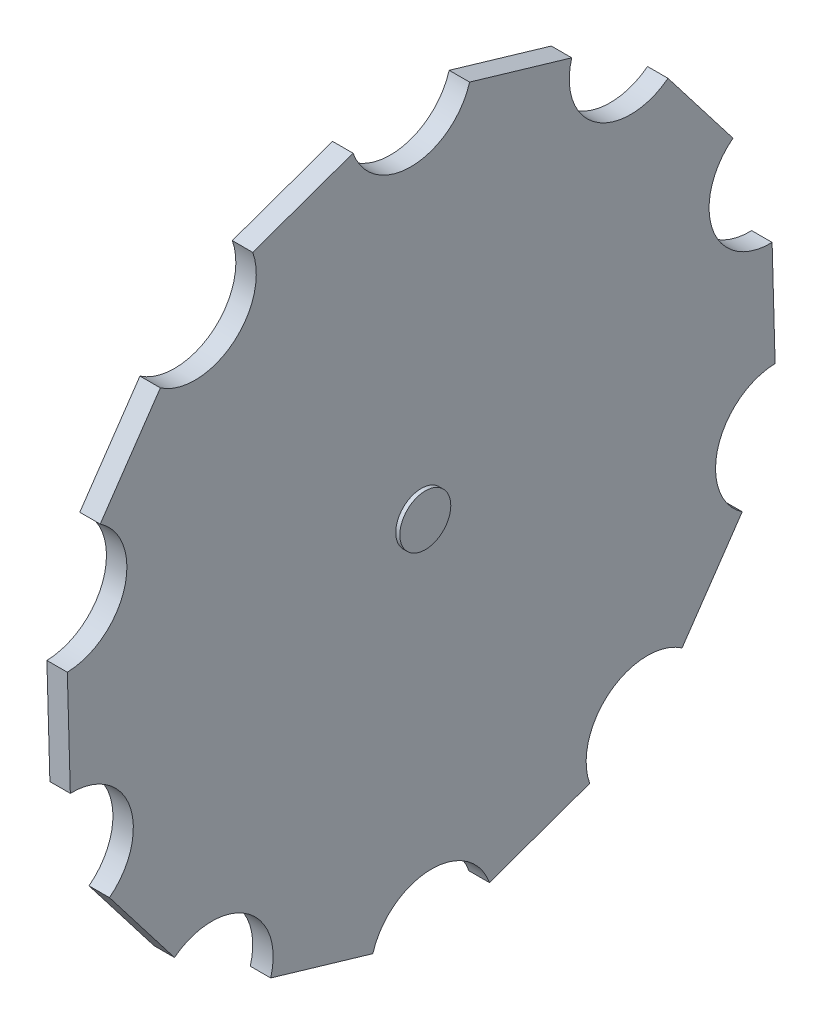
SolidWorks part; units mm, degrees
ref_plane "Płaszczyzna przednia" through (0, 0, 0) normal (0, 0, 1) x (1, 0, 0)
ref_plane "Płaszczyzna górna" through (0, 0, 0) normal (0, 1, 0) x (1, 0, 0)
ref_plane "Płaszczyzna prawa" through (0, 0, 0) normal (1, 0, 0) x (0, 0, -1)
sketch "Szkic1" plane through (0, 0, 0) normal (1, 0, 0) x (0, 0, -1)
  line L0 (16.6837, -85.628) -> (41.227, -76.8819)
  line L1 (36.8335, 79.0809) -> (11.8367, 86.4314)
  line L2 (-16.6837, 85.628) -> (-41.227, 76.8819)
  line L3 (-63.8283, 59.4681) -> (-78.5434, 37.9662)
  line L4 (-86.5926, 10.5934) -> (-85.8589, -15.4514)
  line L5 (-76.2815, -42.3276) -> (-60.3792, -62.9671)
  line L6 (-36.8335, -79.0809) -> (-11.8367, -86.4314)
  line L7 (63.8283, -59.4681) -> (78.5434, -37.9662)
  line L8 (86.5926, -10.5934) -> (85.8589, 15.4514)
  line L9 (76.2815, 42.3276) -> (60.3792, 62.9671)
  arc A0 (-85.5995, 10.6544) -> (-59.5713, -62.3863) centre (0, 0) ccw construction
  arc A1 (-63.8283, 59.4681) -> (-41.227, 76.8819) centre (-55.3567, 71.8468) ccw
  arc A2 (-16.6837, 85.628) -> (11.8367, 86.4314) centre (-2.554, 90.6631) ccw
  arc A3 (36.8335, 79.0809) -> (60.3792, 62.9671) centre (51.2242, 74.8492) ccw
  arc A4 (76.2815, 42.3276) -> (85.8589, 15.4514) centre (85.4365, 30.4455) ccw
  arc A5 (86.5926, -10.5934) -> (78.5434, -37.9662) centre (87.015, -25.5874) ccw
  arc A6 (63.8283, -59.4681) -> (41.227, -76.8819) centre (55.3567, -71.8468) ccw
  arc A7 (16.6837, -85.628) -> (-11.8367, -86.4314) centre (2.554, -90.6631) ccw
  arc A8 (-36.8335, -79.0809) -> (-60.3792, -62.9671) centre (-51.2242, -74.8492) ccw
  arc A9 (-76.2815, -42.3276) -> (-85.8589, -15.4514) centre (-85.4365, -30.4455) ccw
  arc A10 (-86.5926, 10.5934) -> (-78.5434, 37.9662) centre (-87.015, 25.5874) ccw
  arc A11 (-62.9889, 58.9337) -> (-77.7414, 37.3773) centre (0, 0) ccw construction
  arc A12 (-16.3188, 84.7023) -> (-40.9243, 75.9341) centre (0, 0) ccw construction
  arc A13 (36.5846, 78.1175) -> (11.5245, 85.4867) centre (0, 0) ccw construction
  arc A14 (75.5139, 41.6945) -> (59.5713, 62.3863) centre (0, 0) ccw construction
  arc A15 (85.5995, -10.6544) -> (84.8639, 15.4564) centre (0, 0) ccw construction
  arc A16 (62.9889, -58.9337) -> (77.7414, -37.3773) centre (0, 0) ccw construction
  arc A17 (16.3188, -84.7023) -> (40.9243, -75.9341) centre (0, 0) ccw construction
  arc A18 (-36.5846, -78.1175) -> (-11.5245, -85.4867) centre (0, 0) ccw construction
  point P44 (0, 0)
  dimension "D1" = 10
extrude "Dodanie-wyciągnięcie1" add sketch "Szkic1" along normal blind 5
sketch "Szkic2" plane through (5, 0, 0) normal (1, 0, 0) x (0, 0, -1)
  circle A0 centre (0, 0) radius 6.2359
extrude "Dodanie-wyciągnięcie2" add sketch "Szkic2" along normal blind 1
